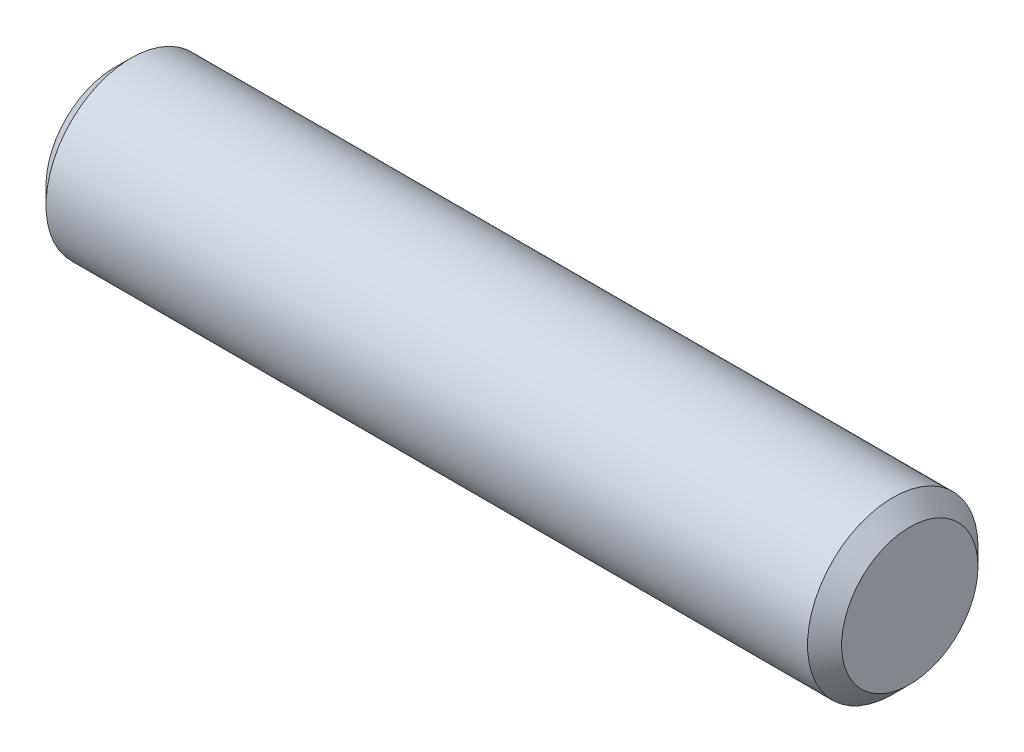
SolidWorks part; units mm, degrees
ref_plane "Front Plane" through (0, 0, 0) normal (0, 0, 1) x (1, 0, 0)
ref_plane "Top Plane" through (0, 0, 0) normal (0, 1, 0) x (1, 0, 0)
ref_plane "Right Plane" through (0, 0, 0) normal (1, 0, 0) x (0, 0, -1)
sketch "Sketch1" plane through (0, 0, 0) normal (1, 0, 0) x (0, 0, -1)
  line L0 (-7, 0) -> (7, 0) construction
  line L1 (0, 1.5) -> (0, -1.5) construction
  circle A0 centre (0, 0) radius 1.5 construction
  point P4 (0, 0)
  point P5 (0, 0)
  dimension "Diameter" = 3
  dimension "Length" = 14
sketch "Sketch2" plane through (0, 0, 0) normal (1, 0, 0) x (0, 0, -1)
  circle A1 centre (0, 0) radius 1.5 construction
  circle A2 centre (0, 0) radius 1.5
extrude "Boss-Extrude1" add sketch "Sketch2" against normal mid plane 14
chamfer "Chamfer2" distance 0.3 angle 45 2 edges at (-7, 0, -1.5) (7, 0, -1.5)
equation "\"D1@Chamfer2\"=\"Diameter@Sketch1\"*.1"
equation "\"D1@Boss-Extrude1\"=\"Length@Sketch1\""
